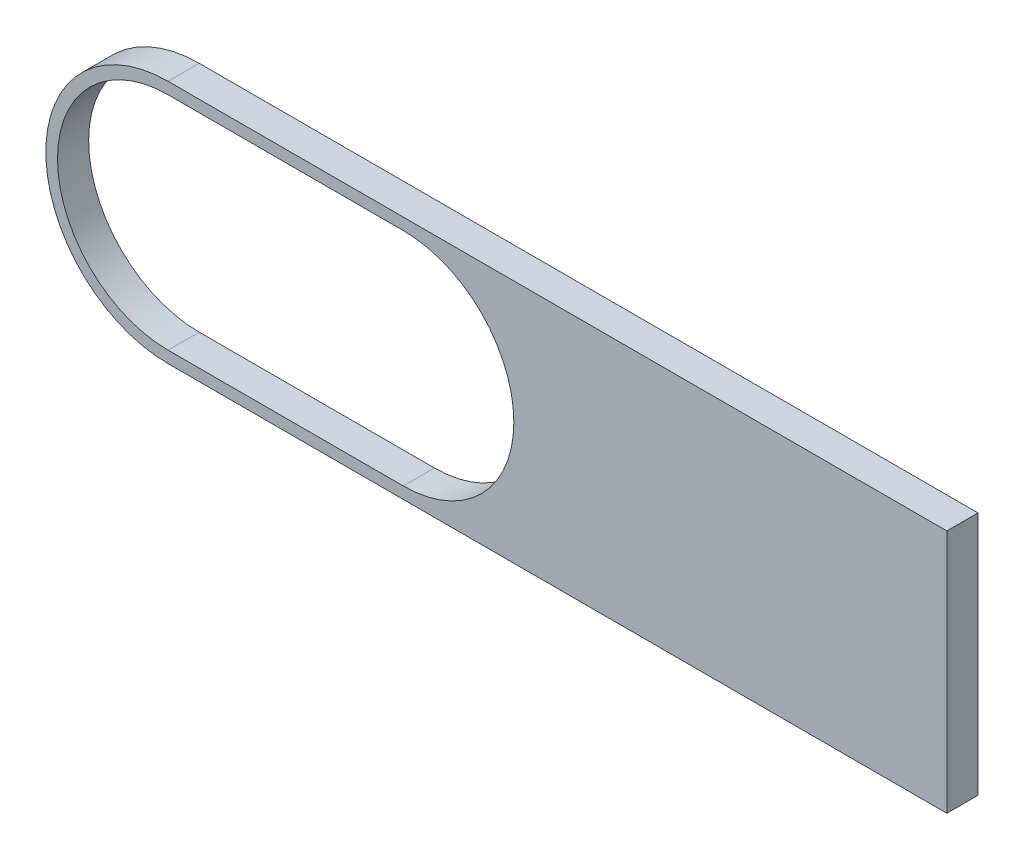
SolidWorks part; units mm, degrees
ref_plane "Front Plane" through (0, 0, 0) normal (0, 0, 1) x (1, 0, 0)
ref_plane "Top Plane" through (0, 0, 0) normal (0, 1, 0) x (1, 0, 0)
ref_plane "Right Plane" through (0, 0, 0) normal (1, 0, 0) x (0, 0, -1)
sketch "Sketch1" plane through (0, 0, 0) normal (0, 0, 1) x (1, 0, 0)
  circle A0 centre (0, 0) radius 19.939
  dimension "D1" = 39.878
extrude "circle extrude" add sketch "Sketch1" along normal blind 5.08
sketch "Sketch3" plane through (0, 0, 0) normal (1, 0, 0) x (0, 0, -1)
  line L0 (0, 55) -> (0, -55) construction
  line L1 (-5.08, 19.939) -> (0, 19.939)
  line L2 (-5.08, 19.939) -> (-5.08, -19.939)
  line L3 (-5.08, -19.939) -> (0, -19.939)
  line L4 (0, 19.939) -> (0, -19.939)
  line L5 (-5.08, -19.939) -> (0, -19.939) construction
extrude "rectangle extrude" add sketch "Sketch3" along normal blind 127
sketch "Sketch2" plane through (0, 0, 5.08) normal (0, 0, 1) x (1, 0, 0)
  circle A0 centre (0, 0) radius 18.034
  dimension "D1" = 36.068
extrude "circle cut" cut sketch "Sketch2" against normal through all
sketch "Sketch6" plane through (0, 0, 5.08) normal (0, 0, 1) x (1, 0, 0)
  line L1 (125.095, -18.034) -> (125.095, 18.034)
  line L3 (0, -18.034) -> (0, 18.034)
  line L4 (0, -18.034) -> (125.095, -18.034)
  line L5 (127, -19.939) -> (0, -19.939) construction
  line L6 (0, 18.034) -> (125.095, 18.034)
  line L8 (127, 19.939) -> (127, -19.939) construction
  arc A0 (0, 19.939) -> (0, -19.939) centre (0, 0) ccw construction
  circle A1 centre (0, 0) radius 18.034 construction
  point P5 (125.095, 0)
  point P12 (0, 0)
  point P17 (-19.939, 0)
  dimension "D1" = 1.905
  dimension "D2" = 1.905
  dimension "D3" = 19.939
extrude "rectangle cut" cut sketch "Sketch6" against normal through all
sketch "Sketch7" plane through (0, 0, 5.08) normal (0, 0, 1) x (1, 0, 0)
  line L0 (0, -18.034) -> (125.095, -18.034) construction
  line L1 (38.354, 18.034) -> (125.095, 18.034)
  line L2 (125.095, -18.034) -> (125.095, 18.034) construction
  line L3 (125.095, 18.034) -> (125.095, -18.034)
  line L4 (125.095, -18.034) -> (38.354, -18.034)
  line L6 (125.095, 18.034) -> (0, 18.034) construction
  arc A0 (38.354, -18.034) -> (38.354, 18.034) centre (38.354, 0) ccw
  dimension "D1" = 38.354
extrude "end shape" add sketch "Sketch7" against normal blind 5.08
